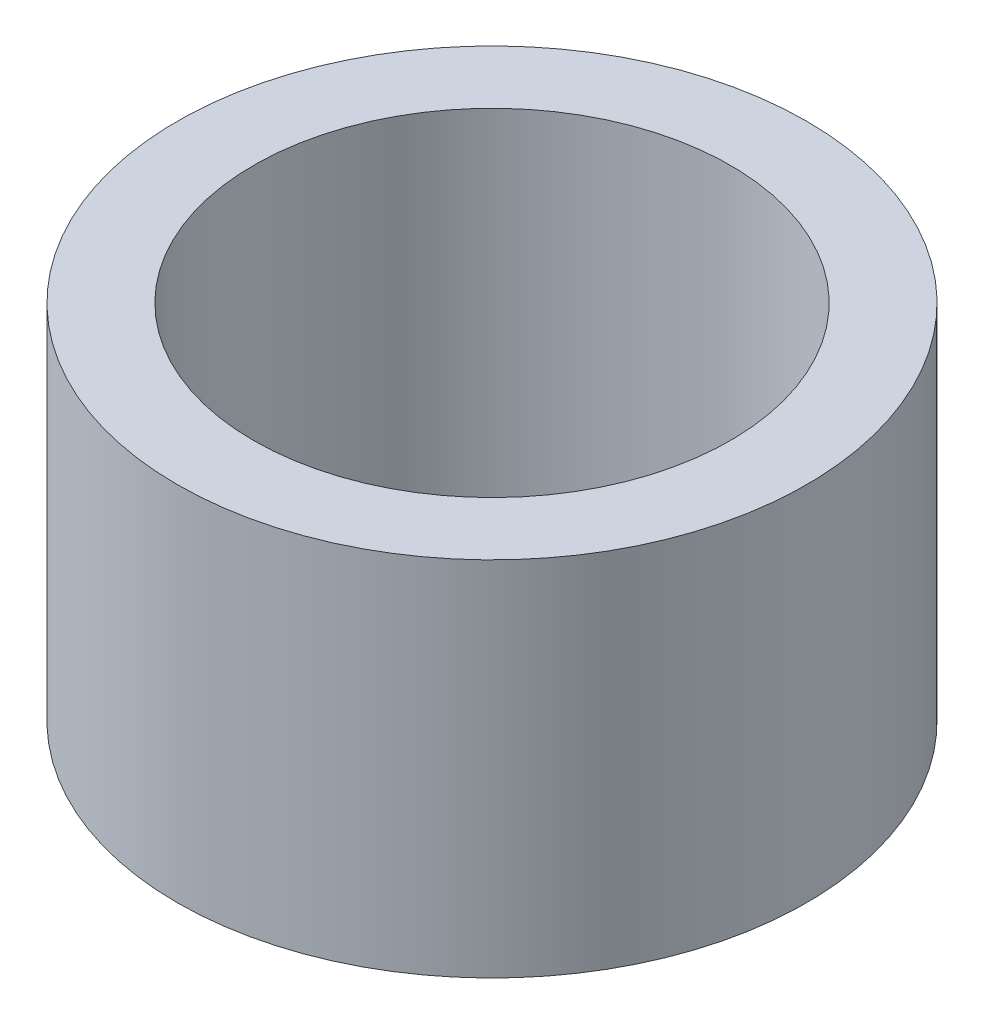
SolidWorks part; units mm, degrees
ref_plane "Front Plane" through (0, 0, 0) normal (0, 0, 1) x (1, 0, 0)
ref_plane "Top Plane" through (0, 0, 0) normal (0, 1, 0) x (1, 0, 0)
ref_plane "Right Plane" through (0, 0, 0) normal (1, 0, 0) x (0, 0, -1)
sketch "Sketch1" plane through (0, 0, 0) normal (0, 1, 0) x (1, 0, 0)
  circle A0 centre (0, 0) radius 14.0462
  circle A1 centre (0, 0) radius 18.542
  dimension "D1" = 37.084
  dimension "D2" = 28.0924
extrude "Boss-Extrude2" add sketch "Sketch1" along normal blind 21.336
